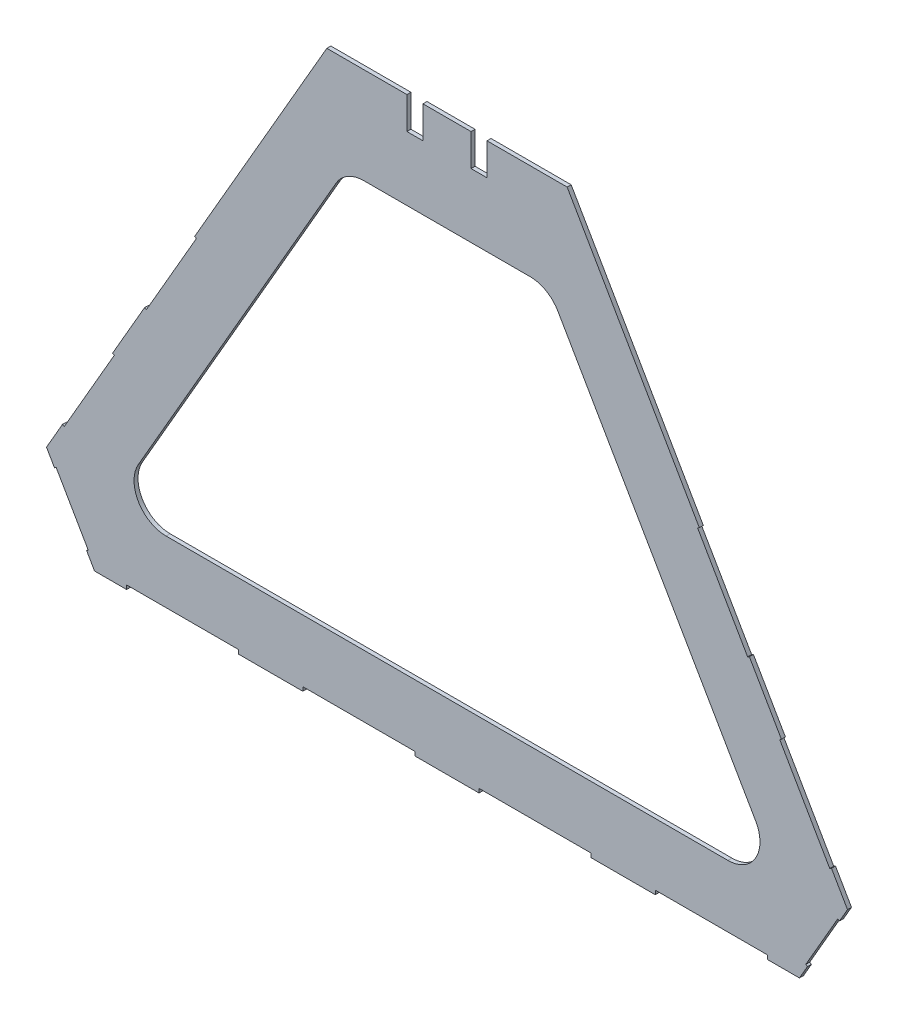
SolidWorks part; units mm, degrees
material "Teak"
ref_plane "Front Plane" through (0, 0, 0) normal (0, 0, 1) x (1, 0, 0)
ref_plane "Top Plane" through (0, 0, 0) normal (0, 1, 0) x (1, 0, 0)
ref_plane "Right Plane" through (0, 0, 0) normal (1, 0, 0) x (0, 0, -1)
sketch "Sketch1" plane through (0, 0, 0) normal (0, 0, 1) x (1, 0, 0)
  line L0 (0, 0) -> (190.5, 0)
  line L1 (190.5, 0) -> (412.75, -384.9483)
  line L2 (412.75, -384.9483) -> (374.65, -450.9394)
  line L3 (374.65, -450.9394) -> (-184.15, -450.9394)
  line L4 (-184.15, -450.9394) -> (-222.25, -384.9483)
  line L5 (-222.25, -384.9483) -> (0, 0)
  dimension "D1" = 444.5
  dimension "D2" = 558.8
  dimension "D3" = 76.2
  dimension "D4" = 76.2
  dimension "D5" = 60
  dimension "D6" = 60
  dimension "D7" = 120
  dimension "D8" = 120
extrude "Boss-Extrude1" add sketch "Sketch1" along normal blind 3.175
sketch "Sketch2" plane through (0, 0, 3.175) normal (0, 0, 1) x (1, 0, 0)
  line L0 (190.5, 0) -> (0, 0) construction
  line L1 (63.5, 0) -> (76.2, 0)
  line L2 (63.5, 0) -> (63.5, -25.4)
  line L3 (63.5, -25.4) -> (76.2, -25.4)
  line L4 (76.2, 0) -> (76.2, -25.4)
  line L5 (29.3294, -76.2) -> (161.1706, -76.2)
  line L6 (114.3, 0) -> (127, 0)
  line L7 (114.3, 0) -> (114.3, -25.4)
  line L8 (114.3, -25.4) -> (127, -25.4)
  line L9 (127, 0) -> (127, -25.4)
  line L10 (183.1677, -88.9) -> (339.953, -360.4601)
  line L11 (317.9559, -398.5601) -> (-127.4559, -398.5601)
  line L12 (-149.453, -360.4601) -> (7.3323, -88.9)
  line L13 (0, 0) -> (-222.25, -384.9483) construction
  line L14 (412.75, -384.9483) -> (190.5, 0) construction
  arc A0 (161.1706, -76.2) -> (183.1677, -88.9) centre (161.1706, -101.6) cw
  arc A1 (29.3294, -76.2) -> (7.3323, -88.9) centre (29.3294, -101.6) ccw
  arc A2 (339.953, -360.4601) -> (317.9559, -398.5601) centre (317.9559, -373.1601) cw
  arc A3 (-127.4559, -398.5601) -> (-149.453, -360.4601) centre (-127.4559, -373.1601) cw
  point P26 (361.95, -398.5601)
  point P29 (-171.45, -398.5601)
  dimension "D11" = 25.4
  dimension "D1" = 63.5
  dimension "D2" = 63.5
  dimension "D3" = 12.7
  dimension "D4" = 25.4
  dimension "D5" = 25.4
  dimension "D6" = 12.7
  dimension "D7" = 50.8
  dimension "D8" = 50.8
  dimension "D9" = 76.2
  dimension "D10" = 533.4
extrude "Cut-Extrude1" cut sketch "Sketch2" against normal through all
sketch "Sketch4" plane through (0, 0, 3.175) normal (0, 0, 1) x (1, 0, 0)
  line L0 (-184.15, -450.9394) -> (374.65, -450.9394) construction
  line L1 (-158.75, -450.9394) -> (-69.85, -450.9394)
  line L2 (-158.75, -450.9394) -> (-158.75, -447.7644)
  line L3 (-158.75, -447.7644) -> (-69.85, -447.7644)
  line L4 (-69.85, -450.9394) -> (-69.85, -447.7644)
  line L5 (-19.05, -447.7644) -> (69.85, -447.7644)
  line L6 (-19.05, -450.9394) -> (-19.05, -447.7644)
  line L7 (-19.05, -450.9394) -> (69.85, -450.9394)
  line L8 (69.85, -450.9394) -> (69.85, -447.7644)
  line L9 (120.65, -447.7644) -> (209.55, -447.7644)
  line L10 (120.65, -450.9394) -> (120.65, -447.7644)
  line L11 (120.65, -450.9394) -> (209.55, -450.9394)
  line L12 (209.55, -450.9394) -> (209.55, -447.7644)
  line L13 (260.35, -447.7644) -> (349.25, -447.7644)
  line L14 (260.35, -450.9394) -> (260.35, -447.7644)
  line L15 (260.35, -450.9394) -> (349.25, -450.9394)
  line L16 (349.25, -450.9394) -> (349.25, -447.7644)
  line L17 (-215.9, -395.9468) -> (-214.5252, -395.1531)
  line L18 (-222.25, -384.9483) -> (-184.15, -450.9394) construction
  line L19 (-214.5252, -395.1531) -> (-189.1252, -439.1472)
  line L20 (-189.1252, -439.1472) -> (-190.5, -439.9409)
  line L21 (-215.9, -395.9468) -> (-190.5, -439.9409)
  line L22 (406.4, -395.9468) -> (405.0252, -395.1531)
  line L23 (374.65, -450.9394) -> (412.75, -384.9483) construction
  line L24 (405.0252, -395.1531) -> (379.6252, -439.1472)
  line L25 (379.6252, -439.1472) -> (381, -439.9409)
  line L26 (381, -439.9409) -> (406.4, -395.9468)
  line L37 (95.25, -1000) -> (95.25, 49000) construction
  line L38 (114.3, 0) -> (76.2, 0) construction
  point P7 (-69.85, -449.3519)
  point P51 (95.25, 0)
  dimension "D1" = 25.4
  dimension "D2" = 88.9
  dimension "D3" = 3.175
  dimension "D4" = 4
  dimension "D5" = 50.8
  dimension "D6" = 12.7
  dimension "D7" = 1.5875
  dimension "D8" = 12.7
  dimension "D9" = 50.8
  dimension "D10" = 1.5875
  dimension "D11" = 12.7
  dimension "D12" = 12.7
extrude "Cut-Extrude2" cut sketch "Sketch4" against normal through all
sketch "Sketch5" plane through (0, 0, 3.175) normal (0, 0, 1) x (1, 0, 0)
  line L0 (-209.55, -362.9512) -> (-208.1752, -363.745)
  line L1 (0, 0) -> (-222.25, -384.9483) construction
  line L2 (-208.1752, -363.745) -> (-168.4877, -295.0042)
  line L3 (-168.4877, -295.0042) -> (-169.8625, -294.2105)
  line L4 (-169.8625, -294.2105) -> (-209.55, -362.9512)
  line L5 (-143.0877, -251.0101) -> (-103.4002, -182.2694)
  line L6 (-104.775, -181.4756) -> (-144.4625, -250.2164)
  line L7 (-144.4625, -250.2164) -> (-143.0877, -251.0101)
  line L8 (-103.4002, -182.2694) -> (-104.775, -181.4756)
  line L9 (95.25, -1000) -> (95.25, 49000) construction
  line L10 (114.3, 0) -> (76.2, 0) construction
  line L11 (400.05, -362.9512) -> (398.6752, -363.745)
  line L12 (358.9877, -295.0042) -> (360.3625, -294.2105)
  line L13 (360.3625, -294.2105) -> (400.05, -362.9512)
  line L14 (398.6752, -363.745) -> (358.9877, -295.0042)
  line L15 (334.9625, -250.2164) -> (333.5877, -251.0101)
  line L16 (293.9002, -182.2694) -> (295.275, -181.4756)
  line L17 (295.275, -181.4756) -> (334.9625, -250.2164)
  line L18 (333.5877, -251.0101) -> (293.9002, -182.2694)
  point P6 (-169.1751, -294.6074)
  point P17 (95.25, 0)
  dimension "D1" = 25.4
  dimension "D2" = 79.375
  dimension "D3" = 1.5875
  dimension "D5" = 50.8
  dimension "D4" = 2
extrude "Cut-Extrude3" cut sketch "Sketch5" against normal through all
